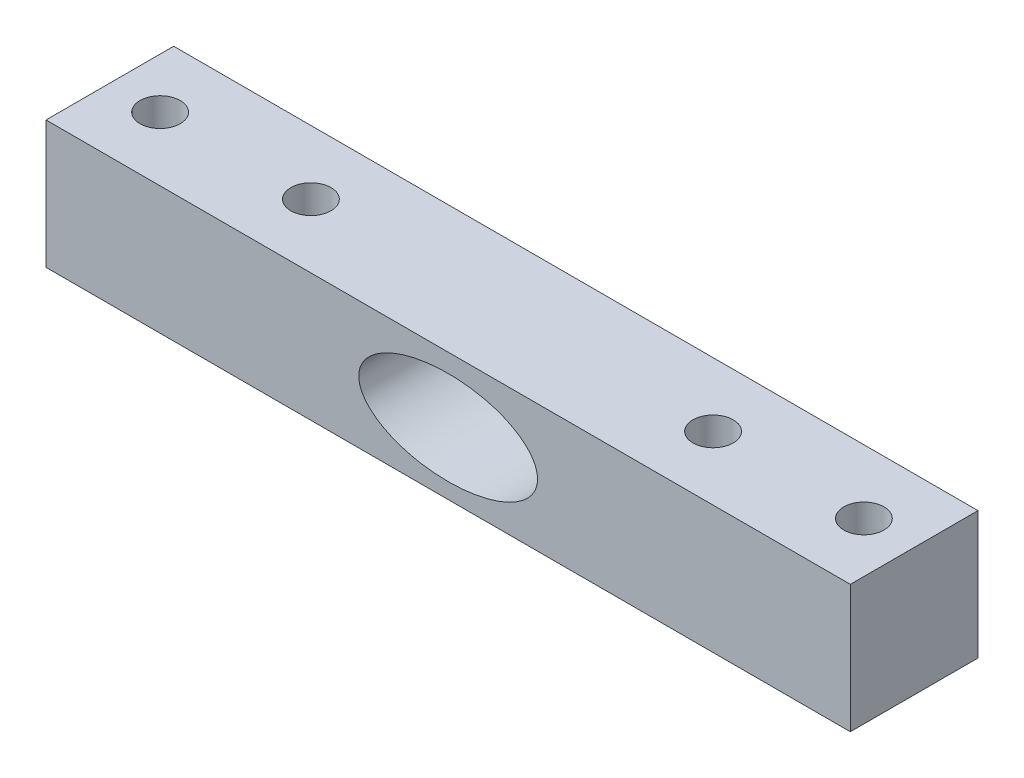
SolidWorks part; units mm, degrees
ref_plane "Front Plane" through (0, 0, 0) normal (0, 0, 1) x (1, 0, 0)
ref_plane "Top Plane" through (0, 0, 0) normal (0, 1, 0) x (1, 0, 0)
ref_plane "Right Plane" through (0, 0, 0) normal (1, 0, 0) x (0, 0, -1)
sketch "Sketch2" plane through (0, 0, 0) normal (0, 1, 0) x (1, 0, 0)
  line L1 (40, -6.35) -> (-40, -6.35)
  line L2 (40, -6.35) -> (40, 6.35)
  line L3 (40, 6.35) -> (-40, 6.35)
  line L4 (-40, -6.35) -> (-40, 6.35)
  line L5 (40, -6.35) -> (-40, 6.35) construction
  line L6 (40, 6.35) -> (-40, -6.35) construction
  point P0 (0, 0)
  dimension "D1" = 80
  dimension "D2" = 12.7
extrude "Boss-Extrude1" add sketch "Sketch2" along normal blind 12.7
sketch "Sketch3" plane through (0, 12.7, 0) normal (0, 1, 0) x (1, 0, 0)
  line L0 (-6.985, 0) -> (6.985, 0) construction
  line L1 (-40, 6.35) -> (-40, -6.35) construction
  line L2 (40, -6.35) -> (40, 6.35) construction
  circle A0 centre (-35, 0) radius 2
  circle A1 centre (-20, 0) radius 2
  circle A2 centre (35, 0) radius 2
  circle A3 centre (20, 0) radius 2
  dimension "D1" = 4
  dimension "D2" = 4
  dimension "D3" = 4
  dimension "D4" = 4
  dimension "D5" = 15
  dimension "D6" = 15
  dimension "D7" = 5
  dimension "D8" = 5
extrude "Cut-Extrude1" cut sketch "Sketch3" against normal through all
sketch "Sketch4" plane through (0, 0, 6.35) normal (0, 0, 1) x (1, 0, 0)
  line L0 (0, -6.985) -> (0, 6.985) construction
  ellipse E0 centre (0, 6.2078) end of major axis (8.89, 6.2078) minor radius 4.6609
  dimension "D1" = 8.89
  dimension "D2" = 4.6609
extrude "Cut-Extrude3" cut sketch "Sketch4" against normal through all contours E0
